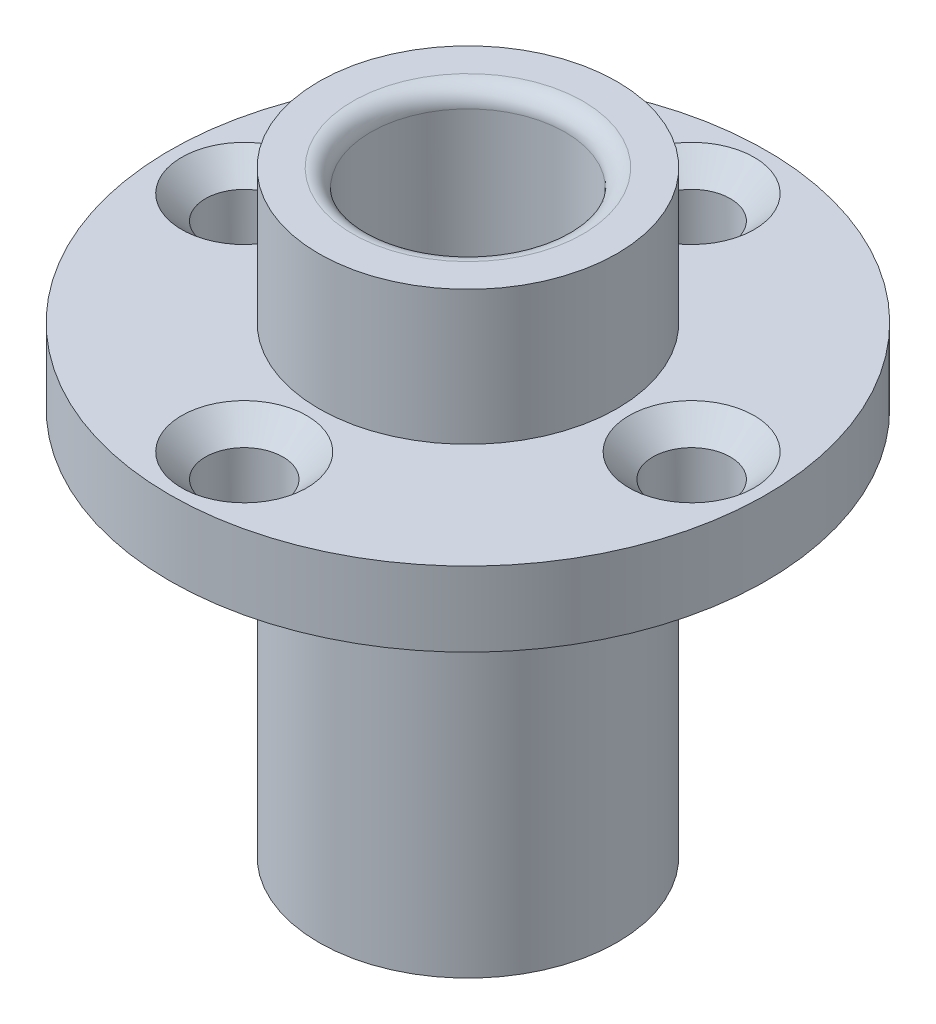
SolidWorks part; units mm, degrees
ref_plane "Front Plane" through (0, 0, 0) normal (0, 0, 1) x (1, 0, 0)
ref_plane "Top Plane" through (0, 0, 0) normal (0, 1, 0) x (1, 0, 0)
ref_plane "Right Plane" through (0, 0, 0) normal (1, 0, 0) x (0, 0, -1)
sketch "Sketch1" plane through (0, 0, 0) normal (0, 0, 1) x (1, 0, 0)
  line L0 (4.1402, 12.7) -> (4.1402, -12.7)
  line L1 (4.1402, -12.7) -> (6.35, -12.7)
  line L2 (6.35, -12.7) -> (6.35, 3.81)
  line L3 (6.35, 3.81) -> (12.7, 3.81)
  line L4 (12.7, 3.81) -> (12.7, 6.985)
  line L5 (12.7, 6.985) -> (6.35, 6.985)
  line L6 (6.35, 6.985) -> (6.35, 12.7)
  line L7 (6.35, 12.7) -> (4.1402, 12.7)
  line L8 (0, 0) -> (0, -6.4917) construction
  point P2 (4.1402, 0)
  dimension "D1" = 16.51
  dimension "D2" = 8.89
  dimension "D3" = 8.2804
  dimension "D4" = 3.175
  dimension "D5" = 6.35
  dimension "D6" = 6.35
revolve "Revolve1" add sketch "Sketch1" angle 360 about L8
sketch "Sketch2" plane through (0, 6.985, 0) normal (0, 1, 0) x (1, 0, 0)
  line L0 (0, 6.35) -> (0, 12.7) construction
  circle A0 centre (0, 0) radius 6.35 construction
  circle A1 centre (0, 0) radius 6.35 construction
  circle A2 centre (0, 0) radius 12.7 construction
  circle A3 centre (0, 9.525) radius 1.65
  dimension "D1" = 3.3
extrude "Cut-Extrude1" cut sketch "Sketch2" against normal through all
chamfer "Chamfer1" distance 1.016 angle 45 1 edges at (0, 6.985, -7.875)
pattern_circular "CirPattern1" count 4 over 360 about axis through (0, 0, 0) along (0, 1, 0) of "Cut-Extrude1", "Chamfer1"
fillet "Fillet1" radius 0.762 2 edges at (0, -12.7, 4.1402) (0, 12.7, 4.1402)
